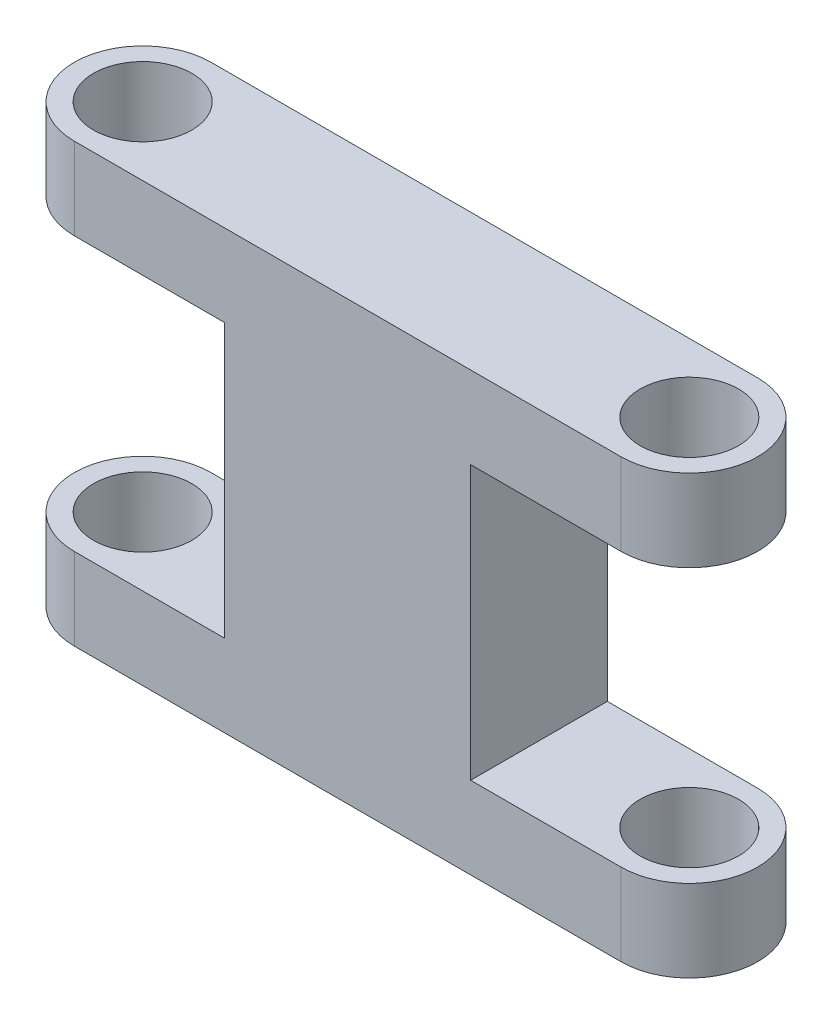
SolidWorks part; units mm, degrees
ref_plane "前视基准面" through (0, 0, 0) normal (0, 0, 1) x (1, 0, 0)
ref_plane "上视基准面" through (0, 0, 0) normal (0, 1, 0) x (1, 0, 0)
ref_plane "右视基准面" through (0, 0, 0) normal (1, 0, 0) x (0, 0, -1)
other "Configuration Table"
sketch "草图1" plane through (0, 0, 0) normal (0, 1, 0) x (1, 0, 0)
  line L0 (0, -4) -> (9976.5942, -4) construction
  line L1 (4, -1.5) -> (24, -1.5)
  line L3 (4, -6.5) -> (24, -6.5)
  line L5 (14, 0) -> (14, -9976.5942) construction
  circle A0 centre (4, -4) radius 1.8
  circle A1 centre (4, -4) radius 2.5
  circle A2 centre (24, -4) radius 2.5
  circle A3 centre (24, -4) radius 1.8
  point P0 (0, 0)
  point P10 (14, -1.5)
  dimension "D1" = 3.6
  dimension "D2" = 5
  dimension "D3" = 20
extrude "凸台-拉伸1" add sketch "草图1" along normal blind 16 contours L3 A2 L1 A1 | A1 A0 | A2 A3
sketch "草图2" plane through (0, 0, 6.5) normal (0, 0, 1) x (1, 0, 0)
  line L0 (14, 16) -> (14, -49984) construction
  line L1 (4, 16) -> (24, 16) construction
  line L2 (0, 8) -> (50000, 8) construction
  line L3 (1.5, 16) -> (1.5, 0) construction
  line L4 (18.5, 13) -> (18.5, 3)
  line L5 (1.5, 13) -> (9.5, 13)
  line L6 (1.5, 13) -> (1.5, 3)
  line L7 (1.5, 3) -> (9.5, 3)
  line L8 (9.5, 13) -> (9.5, 3)
  line L9 (26.5, 3) -> (18.5, 3)
  line L10 (26.5, 13) -> (26.5, 3)
  line L11 (26.5, 13) -> (18.5, 13)
  point P4 (14, 16)
  point P9 (1.5, 8)
  point P14 (9.5, 8)
  dimension "D1" = 10
  dimension "D2" = 8
extrude "切除-拉伸1" cut sketch "草图2" against normal up to next
